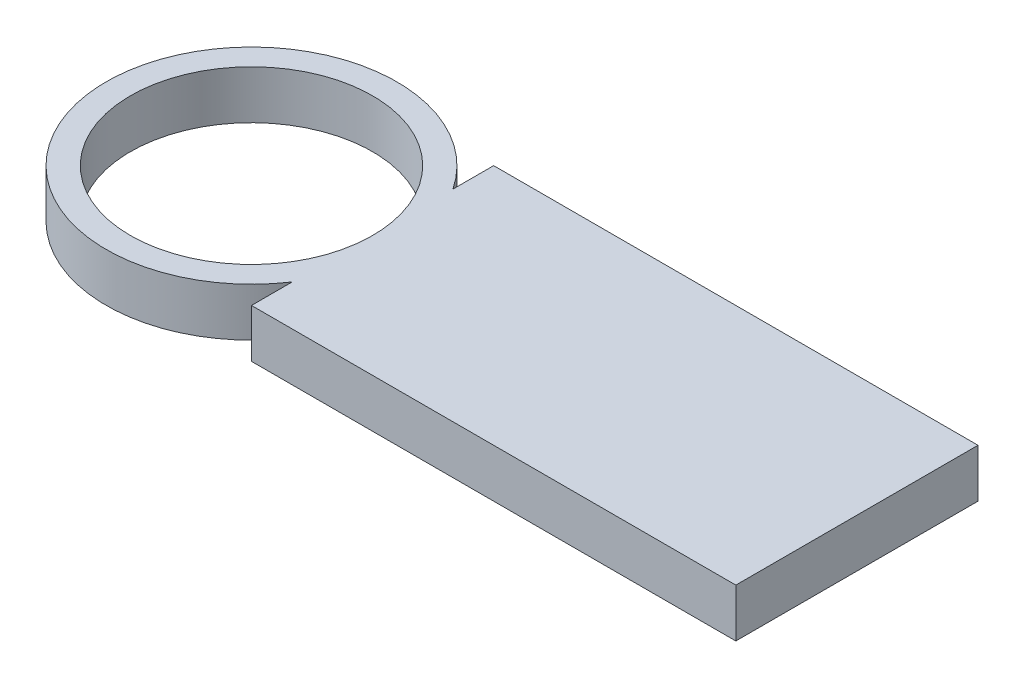
SolidWorks part; units mm, degrees
ref_plane "Front Plane" through (0, 0, 0) normal (0, 0, 1) x (1, 0, 0)
ref_plane "Top Plane" through (0, 0, 0) normal (0, 1, 0) x (1, 0, 0)
ref_plane "Right Plane" through (0, 0, 0) normal (1, 0, 0) x (0, 0, -1)
sketch "Sketch1" plane through (0, 0, 0) normal (0, 1, 0) x (1, 0, 0)
  circle A0 centre (0, 0) radius 30
  circle A1 centre (0, 0) radius 25
  dimension "D1" = 5
extrude "Boss-Extrude1" add sketch "Sketch1" along normal blind 10
sketch "Sketch3" plane through (0, 0, 0) normal (0, 1, 0) x (1, 0, 0)
  line L0 (0, 0) -> (25, 0) construction
  line L1 (125, 25) -> (25, 25)
  line L2 (125, 25) -> (125, -25)
  line L3 (125, -25) -> (25, -25)
  line L4 (25, 25) -> (25, -25)
  line L5 (125, 25) -> (25, -25) construction
  line L6 (125, -25) -> (25, 25) construction
  line L7 (25, 0) -> (25, 50) construction
  line L8 (25, -50) -> (25, 50) construction
  circle A0 centre (0, 0) radius 25 construction
  point P0 (75, 0)
  point P14 (25, 0)
  dimension "D1" = 100
  dimension "D2" = 100
  dimension "D3" = 50
  dimension "D4" = 25
extrude "Boss-Extrude2" add sketch "Sketch3" along normal blind 10
